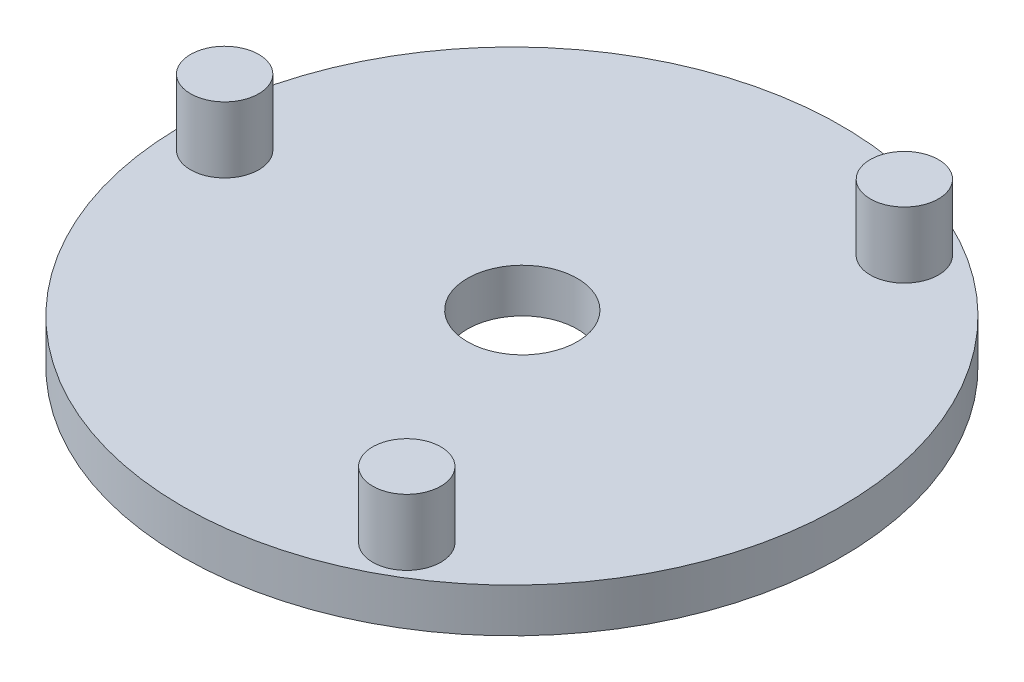
SolidWorks part; units mm, degrees
ref_plane "Front Plane" through (0, 0, 0) normal (0, 0, 1) x (1, 0, 0)
ref_plane "Top Plane" through (0, 0, 0) normal (0, 1, 0) x (1, 0, 0)
ref_plane "Right Plane" through (0, 0, 0) normal (1, 0, 0) x (0, 0, -1)
sketch "Sketch1" plane through (0, 0, 0) normal (0, 1, 0) x (1, 0, 0)
  circle A0 centre (0, 0) radius 150
  circle A1 centre (0, 4.7242) radius 25
  dimension "D1" = 300
extrude "Boss-Extrude1" add sketch "Sketch1" along normal blind 20
sketch "Sketch2" plane through (0, 20, 0) normal (0, 1, 0) x (1, 0, 0)
  circle A0 centre (0, 0) radius 130.7532 construction
  circle A1 centre (-130.7532, 0) radius 15.5177
  circle A2 centre (65.3766, 113.2356) radius 15.5177
  circle A3 centre (65.3766, -113.2356) radius 15.5177
  point P11 (0, 0)
  dimension "D1" = 3
extrude "Boss-Extrude2" add sketch "Sketch2" along normal blind 30
sketch "Sketch3" plane through (0, 0, 0) normal (0, -1, 0) x (1, 0, 0)
  circle A0 centre (0, -4.7242) radius 106.6349 construction
  circle A1 centre (-103.0069, 22.8544) radius 15.0121
  circle A2 centre (22.8544, 103.0069) radius 15.0121
  circle A3 centre (103.0069, -22.8544) radius 15.0121
  circle A4 centre (-22.8544, -103.0069) radius 15.0121
  point P14 (0, 0)
  dimension "D1" = 4
extrude "Boss-Extrude3" add sketch "Sketch3" along normal blind 20
